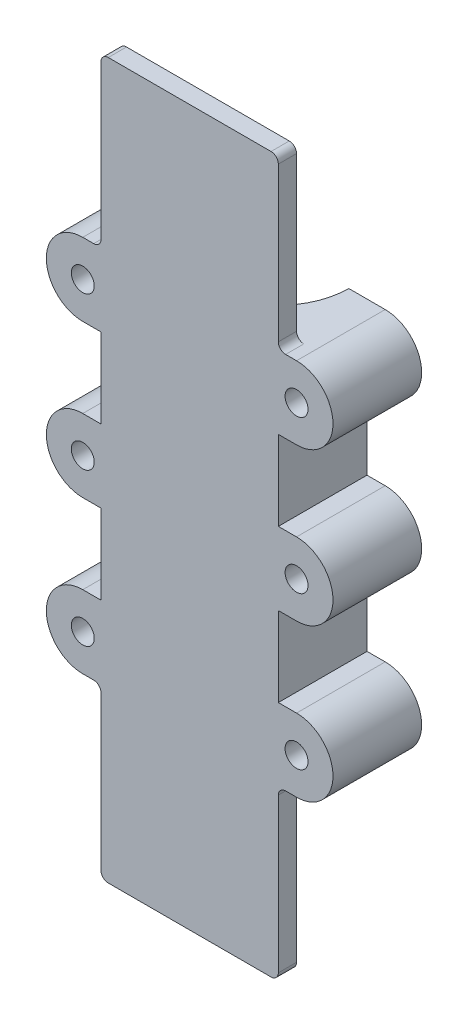
SolidWorks part; units mm, degrees
material "ABS"
ref_plane "X-Y Datum" through (0, 0, 0) normal (0, 0, 1) x (1, 0, 0)
ref_plane "X-Z Datum" through (0, 0, 0) normal (0, 1, 0) x (1, 0, 0)
ref_plane "Y-Z Datum" through (0, 0, 0) normal (1, 0, 0) x (0, 0, -1)
sketch "Sketch1" plane through (0, 0, 0) normal (0, 1, 0) x (1, 0, 0)
  line L0 (-12.2809, 0) -> (-15.4559, 0)
  line L1 (12.2809, 0) -> (15.4559, 0)
  line L3 (0, -15.4559) -> (-15.4559, -15.4559)
  line L4 (-15.4559, -15.4559) -> (-15.4559, 0)
  line L5 (15.4559, 0) -> (15.4559, -15.4559)
  line L6 (15.4559, -15.4559) -> (0, -15.4559)
  arc A0 (-12.2809, 0) -> (12.2809, 0) centre (0, 0) ccw
extrude "Boss-Extrude1" add sketch "Sketch1" along normal blind 65.8876
sketch "Sketch2" plane through (0, 65.8876, 0) normal (0, 1, 0) x (1, 0, 0)
  line L2 (-12.2809, -12.2809) -> (0, -12.2809)
  line L3 (0, -12.2809) -> (12.2809, -12.2809)
  line L6 (15.4559, -12.2809) -> (15.4559, -15.4559)
  line L7 (15.4559, -15.4559) -> (-15.4559, -15.4559)
  line L8 (-15.4559, -15.4559) -> (-15.4559, -12.2809)
  line L9 (-12.2809, -12.2809) -> (-15.4559, -12.2809)
  line L10 (12.2809, -12.2809) -> (15.4559, -12.2809)
  arc A0 (-12.2809, 0) -> (12.2809, 0) centre (0, 0) ccw construction
extrude "Boss-Extrude2" add sketch "Sketch2" along normal blind 29.3624
ref_plane "Plane1" through (0, 32.9438, 0) normal (0, 1, 0) x (1, 0, 0)
mirror "Mirror1" about plane through (0, 32.9438, 0) normal (0, 1, 0) of "Boss-Extrude2"
sketch "Sketch4" plane through (0, 0, 0) normal (0, 0, -1) x (-1, 0, 0)
  line L0 (-15.4559, 39.2938) -> (-15.4559, 26.5938)
  line L1 (-15.4559, 0) -> (-15.4559, 3.175) construction
  line L2 (8.5007, 32.9438) -> (-8.5007, 32.9438) construction
  line L3 (-18.6309, 39.2938) -> (-15.4559, 39.2938)
  line L4 (-18.6309, 26.5938) -> (-15.4559, 26.5938)
  line L5 (-15.4559, 65.8876) -> (-15.4559, 62.7126) construction
  line L6 (-15.4559, 65.8876) -> (-15.4559, 0) construction
  line L7 (-15.4559, 12.7) -> (-18.6309, 12.7)
  line L8 (-15.4559, 0) -> (-15.4559, 12.7)
  line L9 (-18.6309, 65.8876) -> (-15.4559, 65.8876)
  line L10 (-15.4559, 65.8876) -> (-15.4559, 53.1876)
  line L11 (-15.4559, 53.1876) -> (-18.6309, 53.1876)
  line L12 (0, 65.8876) -> (0, 56.8144) construction
  line L13 (-18.6309, 0) -> (-15.4559, 0)
  line L14 (15.4559, 65.8876) -> (15.4559, 62.7126) construction
  line L15 (15.4559, 0) -> (15.4559, 3.175) construction
  line L16 (18.6309, 0) -> (15.4559, 0)
  line L17 (15.4559, 53.1876) -> (18.6309, 53.1876)
  line L18 (15.4559, 65.8876) -> (15.4559, 53.1876)
  line L19 (18.6309, 65.8876) -> (15.4559, 65.8876)
  line L20 (15.4559, 0) -> (15.4559, 12.7)
  line L21 (15.4559, 12.7) -> (18.6309, 12.7)
  line L22 (18.6309, 26.5938) -> (15.4559, 26.5938)
  line L23 (18.6309, 39.2938) -> (15.4559, 39.2938)
  line L24 (15.4559, 39.2938) -> (15.4559, 26.5938)
  arc A0 (-18.6309, 39.2938) -> (-18.6309, 26.5938) centre (-18.6309, 32.9438) ccw
  arc A2 (-18.6309, 65.8876) -> (-18.6309, 53.1876) centre (-18.6309, 59.5376) ccw
  circle A3 centre (-18.6309, 59.5376) radius 2
  circle A4 centre (-18.6309, 32.9438) radius 2
  circle A5 centre (-18.6309, 6.35) radius 2
  arc A6 (-18.6309, 0) -> (-18.6309, 12.7) centre (-18.6309, 6.35) cw
  arc A7 (18.6309, 0) -> (18.6309, 12.7) centre (18.6309, 6.35) ccw
  circle A8 centre (18.6309, 6.35) radius 2
  circle A9 centre (18.6309, 32.9438) radius 2
  circle A10 centre (18.6309, 59.5376) radius 2
  arc A11 (18.6309, 65.8876) -> (18.6309, 53.1876) centre (18.6309, 59.5376) cw
  arc A12 (18.6309, 39.2938) -> (18.6309, 26.5938) centre (18.6309, 32.9438) cw
extrude "Boss-Extrude3" add sketch "Sketch4" against normal through all
fillet "Fillet1" radius 1.27 8 edges at (-15.4559, 0, 13.8684) (-15.4559, 95.25, 13.8684) (15.4559, 95.25, 13.8684) (15.4559, -29.3624, 13.8684) (-15.4559, -29.3624, 13.8684) (15.4559, 65.8876, 13.8684) (15.4559, 0, 13.8684) (-15.4559, 65.8876, 13.8684)
